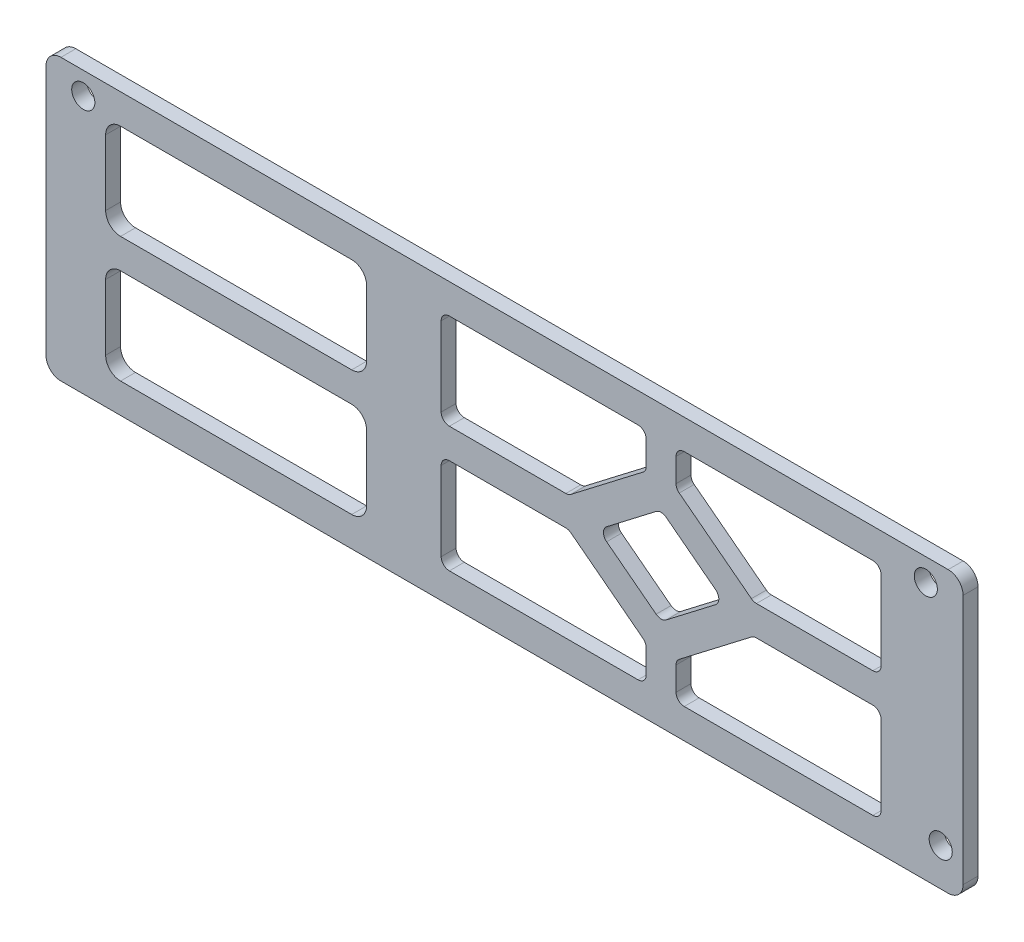
SolidWorks part; units mm, degrees
material "Thornel Mat VMA"
ref_plane "前视基准面" through (0, 0, 0) normal (0, 0, 1) x (1, 0, 0)
ref_plane "上视基准面" through (0, 0, 0) normal (0, 1, 0) x (1, 0, 0)
ref_plane "右视基准面" through (0, 0, 0) normal (1, 0, 0) x (0, 0, -1)
sketch "草图1" plane through (0, 0, 0) normal (0, 0, 1) x (1, 0, 0)
  line L1 (-61.5, -18.8) -> (61.5, -18.8)
  line L2 (-61.5, -18.8) -> (-61.5, 18.8)
  line L3 (-61.5, 18.8) -> (61.5, 18.8)
  line L4 (61.5, -18.8) -> (61.5, 18.8)
  line L5 (0, 18.8) -> (0, -18.8) construction
  line L6 (-61.5, 0) -> (61.5, 0) construction
  point P0 (0, 0)
  dimension "D1" = 37.6
  dimension "D2" = 123
extrude "凸台-拉伸1" add sketch "草图1" along normal blind 2
sketch "草图2" plane through (0, 0, 2) normal (0, 0, 1) x (1, 0, 0)
  circle A6 centre (56.5, 15.8) radius 1.55
  circle A7 centre (58.5, -13.75) radius 1.55
  circle A8 centre (-56.5, 15.8) radius 1.55
  dimension "D1" = 3.1
  dimension "D2" = 113
  dimension "D3" = 56.5
  dimension "D4" = 15.8
  dimension "D5" = 58.5
  dimension "D6" = 13.75
extrude "切除-拉伸1" cut sketch "草图2" against normal blind 10
sketch "草图3" plane through (0, 0, 2) normal (0, 0, 1) x (1, 0, 0)
  line L0 (61.5, 18.8) -> (-61.5, 18.8) construction
  line L1 (-53.5, -14.8) -> (-18.5, -14.8)
  line L2 (-53.5, -14.8) -> (-53.5, 14.8)
  line L3 (-53.5, 14.8) -> (-18.5, 14.8)
  line L4 (-18.5, -14.8) -> (-18.5, 14.8)
  line L5 (-36, 14.8) -> (-36, -14.8) construction
  line L6 (-53.5, 0) -> (-18.5, 0) construction
  line L7 (-61.5, -18.8) -> (61.5, -18.8) construction
  circle A0 centre (-56.5, 15.8) radius 1.55 construction
  point P0 (-36, 0)
  dimension "D1" = 3
  dimension "D2" = 35
  dimension "D3" = 4
  dimension "D4" = 4
extrude "切除-拉伸2" cut sketch "草图3" against normal blind 10
fillet "圆角1" radius 2 8 edges at (61.5, -18.8, 1) (61.5, 18.8, 1) (-53.5, 14.8, 1) (-53.5, -14.8, 1) (-18.5, -14.8, 1) (-18.5, 14.8, 1) (-61.5, -18.8, 1) (-61.5, 18.8, 1)
sketch "草图4" plane through (0, 0, 2) normal (0, 0, 1) x (1, 0, 0)
  line L0 (-18.5, -12.8) -> (-18.5, 12.8) construction
  line L1 (-8.5, -14.8) -> (50.5, -14.8)
  line L2 (-8.5, -14.8) -> (-8.5, 14.8)
  line L3 (-8.5, 14.8) -> (50.5, 14.8)
  line L4 (50.5, -14.8) -> (50.5, 14.8)
  line L5 (21, 14.8) -> (21, -14.8) construction
  line L6 (-8.5, 0) -> (50.5, 0) construction
  line L7 (-20.5, 14.8) -> (-51.5, 14.8) construction
  line L8 (-51.5, -14.8) -> (-20.5, -14.8) construction
  line L9 (21, 9) -> (9.271, 0) construction
  line L10 (9.271, 0) -> (21, -9) construction
  line L11 (21, -9) -> (32.729, 0) construction
  line L12 (32.729, 0) -> (21, 9) construction
  line L13 (36.0144, 0) -> (21, 11.5209)
  line L14 (21, 11.5209) -> (5.9856, 0)
  line L15 (5.9856, 0) -> (21, -11.5209)
  line L16 (21, -11.5209) -> (36.0144, 0)
  line L17 (29.4437, 0) -> (21, 6.4791)
  line L18 (21, 6.4791) -> (12.5563, 0)
  line L19 (12.5563, 0) -> (21, -6.4791)
  line L20 (21, -6.4791) -> (29.4437, 0)
  line L21 (19, 14.8) -> (19, -14.8)
  line L22 (-8.5, -2) -> (50.5, -2)
  line L23 (23, 14.8) -> (23, -14.8)
  line L24 (-8.5, 2) -> (50.5, 2)
  circle A0 centre (56.5, 15.8) radius 1.55 construction
  point P0 (21, 0)
  dimension "D1" = 6
  dimension "D2" = 10
  dimension "D3" = 75
  dimension "D4" = 9
  dimension "D5" = 2
  dimension "D6" = 2
  dimension "D7" = 2
  dimension "D8" = 2
extrude "切除-拉伸3" cut sketch "草图4" against normal blind 10 contours L16 L23 L1 L4 L22 | L13 L24 L4 L3 L23 | L2 L24 L14 L21 L3 | L22 L2 L1 L21 L15 | L24 L23 L22 L20 L17 | L22 L23 L20 | L23 L22 L21 L19 L20 | L22 L19 L21 | L24 L18 L19 L22 L21 | L18 L24 L21 | L21 L24 L23 L17 L18 | L23 L24 L17 | L24 L21 L22 L23
fillet "圆角2" radius 1.1 24 edges at (23, 14.8, 1) (50.5, 14.8, 1) (23, 9.9863, 1) (19, 14.8, 1) (19, 9.9863, 1) (8.5921, 2, 1) (-8.5, 2, 1) (-8.5, 14.8, 1) (19, -9.9863, 1) (19, -14.8, 1) (-8.5, -14.8, 1) (-8.5, -2, 1) (8.5921, -2, 1) (50.5, -2, 1) (50.5, -14.8, 1) (23, -14.8, 1) (23, -9.9863, 1) (33.4079, -2, 1) (29.4437, 0, 1) (21, -6.4791, 1) (12.5563, 0, 1) (21, 6.4791, 1) (50.5, 2, 1) (33.4079, 2, 1)
sketch "草图5" plane through (0, 0, 2) normal (0, 0, 1) x (1, 0, 0)
  line L0 (-18.5, 0) -> (-53.5, 0)
  line L1 (-18.5, -12.8) -> (-18.5, 12.8) construction
  line L2 (-53.5, 12.8) -> (-53.5, -12.8) construction
extrude "拉伸-薄壁1" add sketch "草图5" against normal blind 2 thin thin type mid plane wall 4
fillet "圆角3" radius 2 4 edges at (-53.5, 2, 1) (-18.5, 2, 1) (-53.5, -2, 1) (-18.5, -2, 1)
